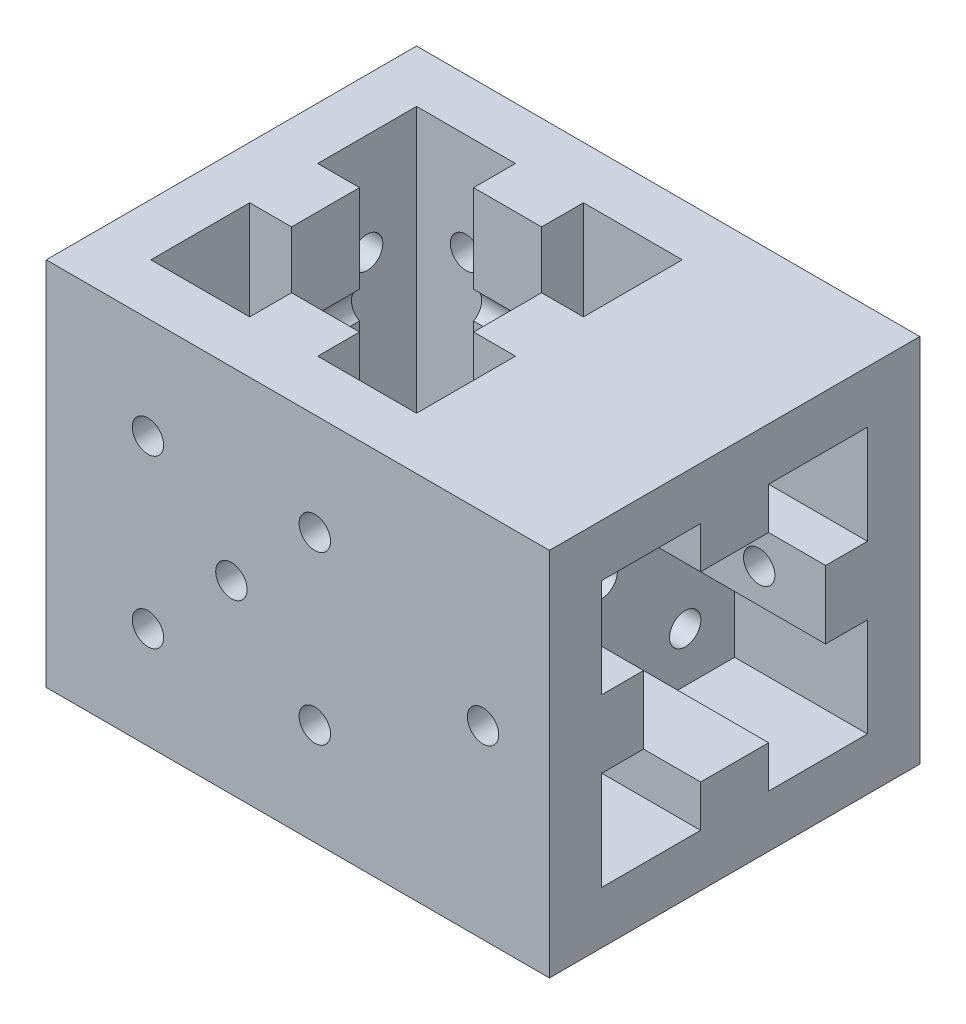
SolidWorks part; units mm, degrees
ref_plane "Front Plane" through (0, 0, 0) normal (0, 0, 1) x (1, 0, 0)
ref_plane "Top Plane" through (0, 0, 0) normal (0, 1, 0) x (1, 0, 0)
ref_plane "Right Plane" through (0, 0, 0) normal (1, 0, 0) x (0, 0, -1)
sketch "Sketch1" plane through (0, 0, 0) normal (0, 1, 0) x (1, 0, 0)
  line L3 (12.7, 12.7) -> (12.7, -12.7) construction
  line L4 (0, 0) -> (12.7, 0) construction
  line L5 (12.7, 3.25) -> (12.7, 12.7)
  line L6 (8.7, -3.25) -> (12.7, -3.25)
  line L7 (8.7, -3.25) -> (8.7, 3.25)
  line L9 (8.7, 3.25) -> (12.7, 3.25)
  line L10 (8.7, -3.25) -> (12.7, 3.25) construction
  line L11 (12.7, -3.25) -> (8.7, 3.25) construction
  line L12 (12.7, -3.25) -> (12.7, -12.7)
  line L13 (-3.25, -12.7) -> (-12.7, -12.7)
  line L14 (-3.25, -8.7) -> (-3.25, -12.7)
  line L15 (-3.25, -8.7) -> (3.25, -8.7)
  line L16 (3.25, -8.7) -> (3.25, -12.7)
  line L17 (3.25, -12.7) -> (12.7, -12.7)
  line L18 (-12.7, 3.25) -> (-12.7, 12.7)
  line L19 (-8.7, 3.25) -> (-12.7, 3.25)
  line L20 (-8.7, 3.25) -> (-8.7, -3.25)
  line L21 (-8.7, -3.25) -> (-12.7, -3.25)
  line L22 (-12.7, -3.25) -> (-12.7, -12.7)
  line L23 (3.25, 12.7) -> (12.7, 12.7)
  line L24 (3.25, 8.7) -> (3.25, 12.7)
  line L25 (3.25, 8.7) -> (-3.25, 8.7)
  line L26 (-3.25, 8.7) -> (-3.25, 12.7)
  line L27 (-3.25, 12.7) -> (-12.7, 12.7)
  line L29 (-17.7, -17.7) -> (17.7, -17.7)
  line L30 (-17.7, -17.7) -> (-17.7, 17.7)
  line L31 (-17.7, 17.7) -> (17.7, 17.7)
  line L32 (17.7, -17.7) -> (17.7, 17.7)
  line L33 (-17.7, -17.7) -> (17.7, 17.7) construction
  line L34 (-17.7, 17.7) -> (17.7, -17.7) construction
  point P10 (10.7, 0)
  point P11 (0, 0)
  point P32 (0, 0)
  dimension "D2" = 25.4
  dimension "D3" = 6.5
  dimension "D4" = 4
  dimension "D1" = 12.7
  dimension "D6" = 5
  dimension "D7" = 5
  dimension "D5" = 4
extrude "Boss-Extrude1" add sketch "Sketch1" along normal blind 35.4
sketch "Sketch2" plane through (17.7, 0, 0) normal (1, 0, 0) x (0, 0, -1)
  line L3 (12.7, 30.4) -> (12.7, 5) construction
  line L4 (0, 17.7) -> (12.7, 17.7) construction
  line L5 (12.7, 20.95) -> (12.7, 30.4)
  line L6 (8.7, 14.45) -> (12.7, 14.45)
  line L7 (8.7, 14.45) -> (8.7, 20.95)
  line L9 (8.7, 20.95) -> (12.7, 20.95)
  line L10 (8.7, 14.45) -> (12.7, 20.95) construction
  line L11 (12.7, 14.45) -> (8.7, 20.95) construction
  line L12 (12.7, 14.45) -> (12.7, 5)
  line L13 (-3.25, 5) -> (-12.7, 5)
  line L14 (-3.25, 9) -> (-3.25, 5)
  line L15 (-3.25, 9) -> (3.25, 9)
  line L16 (3.25, 9) -> (3.25, 5)
  line L17 (3.25, 5) -> (12.7, 5)
  line L18 (-12.7, 20.95) -> (-12.7, 30.4)
  line L19 (-8.7, 20.95) -> (-12.7, 20.95)
  line L20 (-8.7, 20.95) -> (-8.7, 14.45)
  line L21 (-8.7, 14.45) -> (-12.7, 14.45)
  line L22 (-12.7, 14.45) -> (-12.7, 5)
  line L23 (3.25, 30.4) -> (12.7, 30.4)
  line L24 (3.25, 26.4) -> (3.25, 30.4)
  line L25 (3.25, 26.4) -> (-3.25, 26.4)
  line L26 (-3.25, 26.4) -> (-3.25, 30.4)
  line L27 (-3.25, 30.4) -> (-12.7, 30.4)
  line L29 (-17.7, 0) -> (17.7, 0)
  line L30 (-17.7, 0) -> (-17.7, 35.4)
  line L31 (-17.7, 35.4) -> (17.7, 35.4)
  line L32 (17.7, 0) -> (17.7, 35.4)
  line L33 (-17.7, 0) -> (17.7, 35.4) construction
  line L34 (-17.7, 35.4) -> (17.7, 0) construction
  point P10 (10.7, 17.7)
  point P11 (9.3647, 24.2467)
  point P21 (0, 0)
  point P32 (0, 17.7)
  dimension "D1" = 12.7
  dimension "D2" = 25.4
  dimension "D3" = 6.5
  dimension "D4" = 4
  dimension "D6" = 5
  dimension "D7" = 5
  dimension "D5" = 4
extrude "Boss-Extrude2" add sketch "Sketch2" along normal blind 12.7
sketch "Sketch5" plane through (17.7, 0, 0) normal (1, 0, 0) x (0, 0, -1)
  line L1 (12.7, 5) -> (-12.7, 30.4) construction
  line L2 (12.7, 14.45) -> (3.25, 5) construction
  circle A0 centre (0, 17.7) radius 1.5
  circle A1 centre (7.975, 9.725) radius 1.5
  circle A2 centre (-7.975, 9.725) radius 1.5
  circle A3 centre (-7.975, 25.675) radius 1.5
  circle A4 centre (7.975, 25.675) radius 1.5
  point P23 (0, 17.7)
  dimension "D1" = 3
  dimension "D2" = 4
extrude "Cut-Extrude2" cut sketch "Sketch5" against normal through all
sketch "Sketch6" plane through (0, 0, -17.7) normal (0, 0, -1) x (-1, 0, 0)
  line L0 (17.7, 9.725) -> (-30.4, 9.725) construction
  line L1 (17.7, 35.4) -> (17.7, 0) construction
  line L2 (-30.4, 0) -> (-30.4, 35.4) construction
  line L4 (7.975, 0) -> (7.975, 35.4) construction
  line L5 (-30.4, 0) -> (17.7, 0) construction
  line L6 (-30.4, 35.4) -> (17.7, 35.4) construction
  line L7 (3.25, 0) -> (12.7, 0) construction
  line L8 (-17.7, 35.4) -> (-17.7, 0) construction
  line L9 (-17.7, 0) -> (17.7, 35.4) construction
  line L11 (-30.4, 17.7) -> (-17.7, 17.7) construction
  circle A0 centre (7.975, 9.725) radius 1.5
  circle A1 centre (0, 17.7) radius 1.5
  circle A2 centre (-7.975, 9.725) radius 1.5
  circle A3 centre (-7.975, 25.675) radius 1.5
  circle A4 centre (7.975, 25.675) radius 1.5
  circle A5 centre (-24.05, 17.7) radius 1.5
  point P15 (7.975, 0)
  point P33 (0, 17.7)
  dimension "D1" = 35.4
  dimension "D2" = 3
  dimension "D3" = 4
extrude "Cut-Extrude3" cut sketch "Sketch6" against normal through all
equation "\"WallThickness\"=5"
equation "\"D6@Sketch1\"=\"WallThickness\""
equation "\"D7@Sketch1\"=\"WallThickness\""
equation "\"ProfileThickness\"= \"WallThickness\" * 2 + 1in"
equation "\"D1@Boss-Extrude1\"=\"ProfileThickness\""
equation "\"D1@Sketch6\"=\"ProfileThickness\""
